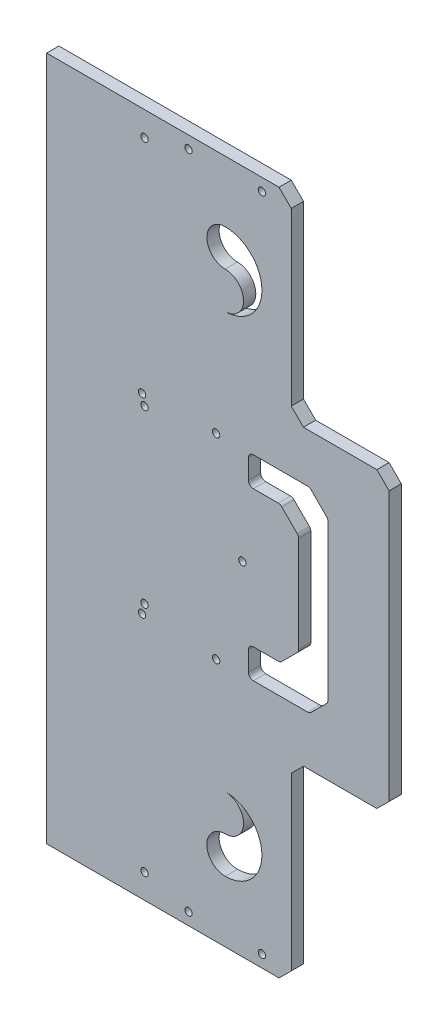
SolidWorks part; units mm, degrees
ref_plane "前视基准面" through (0, 0, 0) normal (0, 0, 1) x (1, 0, 0)
ref_plane "上视基准面" through (0, 0, 0) normal (0, 1, 0) x (1, 0, 0)
ref_plane "右视基准面" through (0, 0, 0) normal (1, 0, 0) x (0, 0, -1)
other "Configuration Table"
sketch "草图1" plane through (0, 0, 0) normal (0, 0, 1) x (1, 0, 0)
  line L0 (-100, -140) -> (-100, -60)
  line L1 (-100, 140) -> (100, 140)
  line L2 (-140, 60) -> (-140, -60)
  line L3 (-100, -140) -> (100, -140)
  line L4 (140, 60) -> (140, -60)
  line L5 (-100, 60) -> (100, -60) construction
  line L6 (-100, -60) -> (100, 60) construction
  line L7 (-100, -60) -> (-140, -60)
  line L8 (140, 60) -> (100, 60)
  line L9 (-140, 60) -> (-100, 60)
  line L10 (-100, 60) -> (-100, 140)
  line L11 (100, 60) -> (100, 140)
  line L12 (100, -140) -> (100, -60)
  line L13 (100, -60) -> (140, -60)
  line L17 (39, -39) -> (-39, -39) construction
  line L20 (-140, 0) -> (140, 0) construction
  line L21 (0, 140) -> (0, -140) construction
  line L22 (39, -39) -> (39, 39) construction
  line L23 (39, 39) -> (-39, 39) construction
  line L24 (-39, -39) -> (-39, 39) construction
  line L25 (39, -39) -> (-39, 39) construction
  line L26 (39, 39) -> (-39, -39) construction
  circle A16 centre (-40, -130) radius 1.5
  circle A17 centre (-40, -35) radius 1.5
  circle A18 centre (40, -130) radius 1.5
  circle A19 centre (40, -35) radius 1.5
  circle A22 centre (-40, 130) radius 1.5
  circle A23 centre (40, 130) radius 1.5
  circle A24 centre (40, 35) radius 1.5
  circle A25 centre (-40, 35) radius 1.5
  circle A34 centre (-39, 39) radius 1.5
  circle A35 centre (39, 39) radius 1.5
  circle A36 centre (39, -39) radius 1.5
  circle A37 centre (-39, -39) radius 1.5
  point P0 (0, 0)
  point P1 (0, 0)
  point P3 (0, 0)
  dimension "D3" = 40
  dimension "D16" = 40
  dimension "D17" = 95
  dimension "D20" = 3
  dimension "D21" = 3
  dimension "D1" = 280
  dimension "D2" = 40
  dimension "D4" = 280
  dimension "D5" = 80
  dimension "D6" = 80
  dimension "D7" = 80
  dimension "D18" = 10
  dimension "D19" = 40
extrude "凸台-拉伸1" add sketch "草图1" along normal blind 5
chamfer "倒角1" distance 5 angle 45 12 edges at (100, 60, 2.5) (100, -60, 2.5) (-100, -60, 2.5) (-100, 60, 2.5) (140, 60, 2.5) (140, -60, 2.5) (-140, -60, 2.5) (-140, 60, 2.5) (100, 140, 2.5) (-100, 140, 2.5) (-100, -140, 2.5) (100, -140, 2.5)
sketch "草图3" plane through (0, 0, 5) normal (0, 0, 1) x (1, 0, 0)
  line L0 (-140, 0) -> (140, 0) construction
  line L1 (-140, 55) -> (-140, -55) construction
  line L2 (140, -55) -> (140, 55) construction
  line L3 (0, 140) -> (0, -140) construction
  line L4 (95, 140) -> (-95, 140) construction
  line L5 (-95, -140) -> (95, -140) construction
  line L11 (-25, -35) -> (25, -35)
  line L12 (-40, -50) -> (-40, -115)
  line L32 (-25, -130) -> (25, -130)
  line L34 (40, -50) -> (40, -115)
  line L35 (-25, 35) -> (25, 35)
  line L37 (40, 50) -> (40, 115)
  line L39 (-25, 130) -> (25, 130)
  line L42 (-40, 50) -> (-40, 115)
  line L43 (-20.0715, -8.1094) -> (-8.4585, -19.9269)
  line L44 (8.1094, -20.0715) -> (19.9269, -8.4585)
  line L45 (19.9269, -8.4585) -> (20.0715, 8.1094)
  line L46 (20.0715, 8.1094) -> (8.4585, 19.9269)
  line L48 (8.4585, 19.9269) -> (-8.1094, 20.0715)
  line L49 (-8.1094, 20.0715) -> (-19.9269, 8.4585)
  line L50 (-19.9269, 8.4585) -> (-20.0715, -8.1094)
  line L51 (-8.4585, -19.9269) -> (8.1094, -20.0715)
  line L52 (-107.5, 40) -> (-82.5, 40)
  line L53 (-107.5, -40) -> (-115, -32.5)
  line L54 (-82.5, 40) -> (-82.5, 28)
  line L55 (-103, -20.5) -> (-95.5, -28)
  line L56 (-82.5, -28) -> (-95.5, -28)
  line L57 (-107.5, 40) -> (-115, 32.5)
  line L58 (-115, 32.5) -> (-115, -32.5)
  line L59 (-103, 20.5) -> (-95.5, 28)
  line L60 (-82.5, 28) -> (-95.5, 28)
  line L61 (-103, 20.5) -> (-103, -20.5)
  line L62 (-82.5, -40) -> (-82.5, -28)
  line L63 (-107.5, -40) -> (-82.5, -40)
  line L64 (107.5, -40) -> (82.5, -40)
  line L65 (82.5, -40) -> (82.5, -28)
  line L66 (82.5, -28) -> (95.5, -28)
  line L67 (103, -20.5) -> (95.5, -28)
  line L68 (103, 20.5) -> (103, -20.5)
  line L69 (103, 20.5) -> (95.5, 28)
  line L70 (82.5, 28) -> (95.5, 28)
  line L71 (82.5, 40) -> (82.5, 28)
  line L72 (107.5, 40) -> (82.5, 40)
  line L73 (107.5, 40) -> (115, 32.5)
  line L74 (115, 32.5) -> (115, -32.5)
  line L75 (107.5, -40) -> (115, -32.5)
  circle A0 centre (-88, 135) radius 1.5
  circle A1 centre (-58, 135) radius 1.5
  circle A42 centre (58, 135) radius 1.5
  circle A43 centre (88, 135) radius 1.5
  circle A84 centre (88, -135) radius 1.5
  circle A85 centre (58, -135) radius 1.5
  circle A86 centre (-58, -135) radius 1.5
  circle A87 centre (-88, -135) radius 1.5
  arc A296 (-25, -130) -> (-40, -115) centre (-40, -130) ccw
  arc A297 (40, -115) -> (25, -130) centre (40, -130) ccw
  arc A298 (-40, -50) -> (-25, -35) centre (-40, -35) ccw
  arc A299 (25, -35) -> (40, -50) centre (40, -35) ccw
  arc A300 (-40, 50) -> (-25, 35) centre (-40, 35) cw
  arc A301 (25, 35) -> (40, 50) centre (40, 35) cw
  arc A302 (40, 115) -> (25, 130) centre (40, 130) cw
  arc A303 (-25, 130) -> (-40, 115) centre (-40, 130) cw
  circle A305 centre (-80, 0) radius 1.5
  arc A313 (-73, -85) -> (-73, -100) centre (-73, -92.5) ccw
  arc A314 (-73, -115) -> (-73, -100) centre (-73, -107.5) ccw
  arc A315 (-73, -85) -> (-73, -115) centre (-73, -100) ccw
  arc A316 (-73, 85) -> (-73, 115) centre (-73, 100) cw
  arc A317 (-73, 85) -> (-73, 100) centre (-73, 92.5) cw
  arc A318 (-73, 115) -> (-73, 100) centre (-73, 107.5) cw
  arc A319 (73, -85) -> (73, -115) centre (73, -100) cw
  arc A320 (73, -85) -> (73, -100) centre (73, -92.5) cw
  arc A332 (73, -115) -> (73, -100) centre (73, -107.5) cw
  arc A333 (73, 85) -> (73, 100) centre (73, 92.5) ccw
  arc A334 (73, 115) -> (73, 100) centre (73, 107.5) ccw
  arc A335 (73, 85) -> (73, 115) centre (73, 100) ccw
  circle A336 centre (0, 0) radius 20 construction
  circle A338 centre (-69.282, 40) radius 1.5
  circle A341 centre (0, 0) radius 80 construction
  circle A343 centre (0, 0) radius 80 construction
  circle A345 centre (0, 0) radius 80 construction
  circle A346 centre (69.282, 40) radius 1.5
  circle A347 centre (0, 0) radius 80 construction
  circle A348 centre (80, 0) radius 1.5
  circle A349 centre (0, 0) radius 80 construction
  circle A350 centre (69.282, -40) radius 1.5
  circle A351 centre (0, 0) radius 80 construction
  circle A353 centre (0, 0) radius 80 construction
  circle A355 centre (0, 0) radius 80 construction
  circle A360 centre (0, 0) radius 80 construction
  circle A361 centre (-69.282, -40) radius 1.5
  circle A366 centre (-40, 69.282) radius 1.5 [skipped]
  circle A367 centre (0, 80) radius 1.5 [skipped]
  circle A368 centre (40, 69.282) radius 1.5 [skipped]
  circle A369 centre (40, -69.282) radius 1.5 [skipped]
  circle A370 centre (0, -80) radius 1.5 [skipped]
  circle A371 centre (-40, -69.282) radius 1.5 [skipped]
  point P2 (0, 0)
  point P61 (0, 0)
  point P95 (-115, 0)
  point P96 (-103, 0)
  point P140 (0, 0)
  point P189 (0, 0)
  point P194 (0, 0)
  dimension "D1" = 12
  dimension "D3" = 12
  dimension "D2" = 25
extrude "切除-拉伸2" cut sketch "草图3" against normal blind 10
fillet "圆角1" radius 10 16 edges at (40, -50, 2.5) (25, -35, 2.5) (-25, -35, 2.5) (-40, -50, 2.5) (25, -130, 2.5) (40, -115, 2.5) (-25, -130, 2.5) (-40, -115, 2.5) (-25, 35, 2.5) (-40, 50, 2.5) (25, 35, 2.5) (40, 50, 2.5) (40, 115, 2.5) (25, 130, 2.5) (-40, 115, 2.5) (-25, 130, 2.5)
fillet "圆角2" radius 2 24 edges at (-82.5, 40, 2.5) (-82.5, 28, 2.5) (-82.5, -40, 2.5) (-82.5, -28, 2.5) (82.5, -40, 2.5) (82.5, -28, 2.5) (82.5, 28, 2.5) (82.5, 40, 2.5) (115, 32.5, 2.5) (107.5, 40, 2.5) (103, 20.5, 2.5) (95.5, 28, 2.5) (107.5, -40, 2.5) (115, -32.5, 2.5) (103, -20.5, 2.5) (95.5, -28, 2.5) (-107.5, -40, 2.5) (-115, -32.5, 2.5) (-95.5, -28, 2.5) (-103, -20.5, 2.5) (-103, 20.5, 2.5) (-95.5, 28, 2.5) (-115, 32.5, 2.5) (-107.5, 40, 2.5)
sketch "草图5" plane through (0, 0, 5) normal (0, 0, 1) x (1, 0, 0)
  line L0 (0, 140) -> (0, -140)
  line L24 (100, 65) -> (100, 135)
  line L25 (100, 135) -> (95, 140)
  line L26 (95, 140) -> (-95, 140)
  line L27 (-95, 140) -> (-100, 135)
  line L28 (-100, 135) -> (-100, 65)
  line L29 (-100, 65) -> (-105, 60)
  line L30 (-105, 60) -> (-135, 60)
  line L31 (-135, 60) -> (-140, 55)
  line L32 (-140, 55) -> (-140, -55)
  line L33 (-140, -55) -> (-135, -60)
  line L34 (-135, -60) -> (-105, -60)
  line L35 (-105, -60) -> (-100, -65)
  line L36 (-100, -65) -> (-100, -135)
  line L37 (-100, -135) -> (-95, -140)
  line L38 (-95, -140) -> (95, -140)
  line L39 (95, -140) -> (100, -135)
  line L40 (100, -135) -> (100, -65)
  line L41 (100, -65) -> (105, -60)
  line L42 (105, -60) -> (135, -60)
  line L43 (135, -60) -> (140, -55)
  line L44 (140, -55) -> (140, 55)
  line L45 (140, 55) -> (135, 60)
  line L46 (135, 60) -> (105, 60)
  line L47 (105, 60) -> (100, 65)
  line L48 (100, 65) -> (100, 135)
  line L49 (100, 135) -> (95, 140)
  line L50 (95, 140) -> (-95, 140)
  line L51 (-95, 140) -> (-100, 135)
  line L52 (-100, 135) -> (-100, 65)
  line L53 (-100, 65) -> (-105, 60)
  line L54 (-105, 60) -> (-135, 60)
  line L55 (-135, 60) -> (-140, 55)
  line L56 (-140, 55) -> (-140, -55)
  line L57 (-140, -55) -> (-135, -60)
  line L58 (-135, -60) -> (-105, -60)
  line L59 (-105, -60) -> (-100, -65)
  line L60 (-100, -65) -> (-100, -135)
  line L61 (-100, -135) -> (-95, -140)
  line L62 (-95, -140) -> (95, -140)
  line L63 (95, -140) -> (100, -135)
  line L64 (100, -135) -> (100, -65)
  line L65 (100, -65) -> (105, -60)
  line L66 (105, -60) -> (135, -60)
  line L67 (135, -60) -> (140, -55)
  line L68 (140, -55) -> (140, 55)
  line L69 (140, 55) -> (135, 60)
  line L70 (135, 60) -> (105, 60)
  line L71 (105, 60) -> (100, 65)
  dimension "D1" = 0
extrude "切除-拉伸3" cut sketch "草图5" against normal through all contours L61 L62 L0 L50 L51 L52 L53 L54 L55 L56 L57 L58 L59 L60
sketch "草图6" plane through (0, 0, 0) normal (0, 0, -1) x (-1, 0, 0)
  line L0 (0, 140) -> (0, -140)
  line L29 (0, 130) -> (0, 140)
  line L30 (0, 140) -> (-95, 140)
  line L31 (-95, 140) -> (-100, 135)
  line L32 (-100, 135) -> (-100, 65)
  line L33 (-100, 65) -> (-105, 60)
  line L34 (-105, 60) -> (-135, 60)
  line L35 (-135, 60) -> (-140, 55)
  line L36 (-140, 55) -> (-140, -55)
  line L37 (-140, -55) -> (-135, -60)
  line L38 (-135, -60) -> (-105, -60)
  line L39 (-105, -60) -> (-100, -65)
  line L40 (-100, -65) -> (-100, -135)
  line L41 (-100, -135) -> (-95, -140)
  line L42 (-95, -140) -> (0, -140)
  line L43 (0, -140) -> (0, -130)
  line L44 (0, -130) -> (-17.0871, -130)
  line L45 (-40, -107.0871) -> (-40, -57.9129)
  line L46 (-17.0871, -35) -> (0, -35)
  line L47 (0, -35) -> (0, -20.0008)
  line L48 (0, -20.0008) -> (-8.1094, -20.0715)
  line L49 (-8.1094, -20.0715) -> (-19.9269, -8.4585)
  line L50 (-19.9269, -8.4585) -> (-20.0715, 8.1094)
  line L51 (-20.0715, 8.1094) -> (-8.4585, 19.9269)
  line L52 (-8.4585, 19.9269) -> (0, 20.0008)
  line L53 (0, 20.0008) -> (0, 35)
  line L54 (0, 35) -> (-17.0871, 35)
  line L55 (-40, 57.9129) -> (-40, 107.0871)
  line L56 (-17.0871, 130) -> (0, 130)
  line L57 (0, 130) -> (0, 140)
  line L58 (0, 140) -> (-95, 140)
  line L59 (-95, 140) -> (-100, 135)
  line L60 (-100, 135) -> (-100, 65)
  line L61 (-100, 65) -> (-105, 60)
  line L62 (-105, 60) -> (-135, 60)
  line L63 (-135, 60) -> (-140, 55)
  line L64 (-140, 55) -> (-140, -55)
  line L65 (-140, -55) -> (-135, -60)
  line L66 (-135, -60) -> (-105, -60)
  line L67 (-105, -60) -> (-100, -65)
  line L68 (-100, -65) -> (-100, -135)
  line L69 (-100, -135) -> (-95, -140)
  line L70 (-95, -140) -> (0, -140)
  line L71 (0, -140) -> (0, -130)
  line L72 (0, -130) -> (-17.0871, -130)
  line L73 (-40, -107.0871) -> (-40, -57.9129)
  line L74 (-17.0871, -35) -> (0, -35)
  line L75 (0, -35) -> (0, -20.0008)
  line L76 (0, -20.0008) -> (-8.1094, -20.0715)
  line L77 (-8.1094, -20.0715) -> (-19.9269, -8.4585)
  line L78 (-19.9269, -8.4585) -> (-20.0715, 8.1094)
  line L79 (-20.0715, 8.1094) -> (-8.4585, 19.9269)
  line L80 (-8.4585, 19.9269) -> (0, 20.0008)
  line L81 (0, 20.0008) -> (0, 35)
  line L82 (0, 35) -> (-17.0871, 35)
  line L83 (-40, 57.9129) -> (-40, 107.0871)
  line L84 (-17.0871, 130) -> (0, 130)
  arc A12 (-26.2523, -124) -> (-17.0871, -130) centre (-17.0871, -120) ccw
  arc A13 (-26.2523, -124) -> (-34, -116.2523) centre (-40, -130) ccw
  arc A14 (-40, -107.0871) -> (-34, -116.2523) centre (-30, -107.0871) ccw
  arc A15 (-34, -48.7477) -> (-40, -57.9129) centre (-30, -57.9129) ccw
  arc A16 (-34, -48.7477) -> (-26.2523, -41) centre (-40, -35) ccw
  arc A17 (-17.0871, -35) -> (-26.2523, -41) centre (-17.0871, -45) ccw
  arc A18 (-26.2523, 41) -> (-17.0871, 35) centre (-17.0871, 45) ccw
  arc A19 (-26.2523, 41) -> (-34, 48.7477) centre (-40, 35) ccw
  arc A20 (-40, 57.9129) -> (-34, 48.7477) centre (-30, 57.9129) ccw
  arc A21 (-34, 116.2523) -> (-40, 107.0871) centre (-30, 107.0871) ccw
  arc A22 (-34, 116.2523) -> (-26.2523, 124) centre (-40, 130) ccw
  arc A23 (-17.0871, 130) -> (-26.2523, 124) centre (-17.0871, 120) ccw
  arc A24 (-26.2523, -124) -> (-17.0871, -130) centre (-17.0871, -120) ccw
  arc A25 (-26.2523, -124) -> (-34, -116.2523) centre (-40, -130) ccw
  arc A26 (-40, -107.0871) -> (-34, -116.2523) centre (-30, -107.0871) ccw
  arc A27 (-34, -48.7477) -> (-40, -57.9129) centre (-30, -57.9129) ccw
  arc A28 (-34, -48.7477) -> (-26.2523, -41) centre (-40, -35) ccw
  arc A29 (-17.0871, -35) -> (-26.2523, -41) centre (-17.0871, -45) ccw
  arc A30 (-26.2523, 41) -> (-17.0871, 35) centre (-17.0871, 45) ccw
  arc A31 (-26.2523, 41) -> (-34, 48.7477) centre (-40, 35) ccw
  arc A32 (-40, 57.9129) -> (-34, 48.7477) centre (-30, 57.9129) ccw
  arc A33 (-34, 116.2523) -> (-40, 107.0871) centre (-30, 107.0871) ccw
  arc A34 (-34, 116.2523) -> (-26.2523, 124) centre (-40, 130) ccw
  arc A35 (-17.0871, 130) -> (-26.2523, 124) centre (-17.0871, 120) ccw
  dimension "D1" = 0
extrude "凸台-拉伸2" add sketch "草图6" against normal blind 5 contours L84 A35 A34 A33 L83 A32 A31 A30 L82 L0 | L80 L79 L78 L77 L76 L0 | L74 A29 A28 A27 L73 A26 A25 A24 L72 L0
